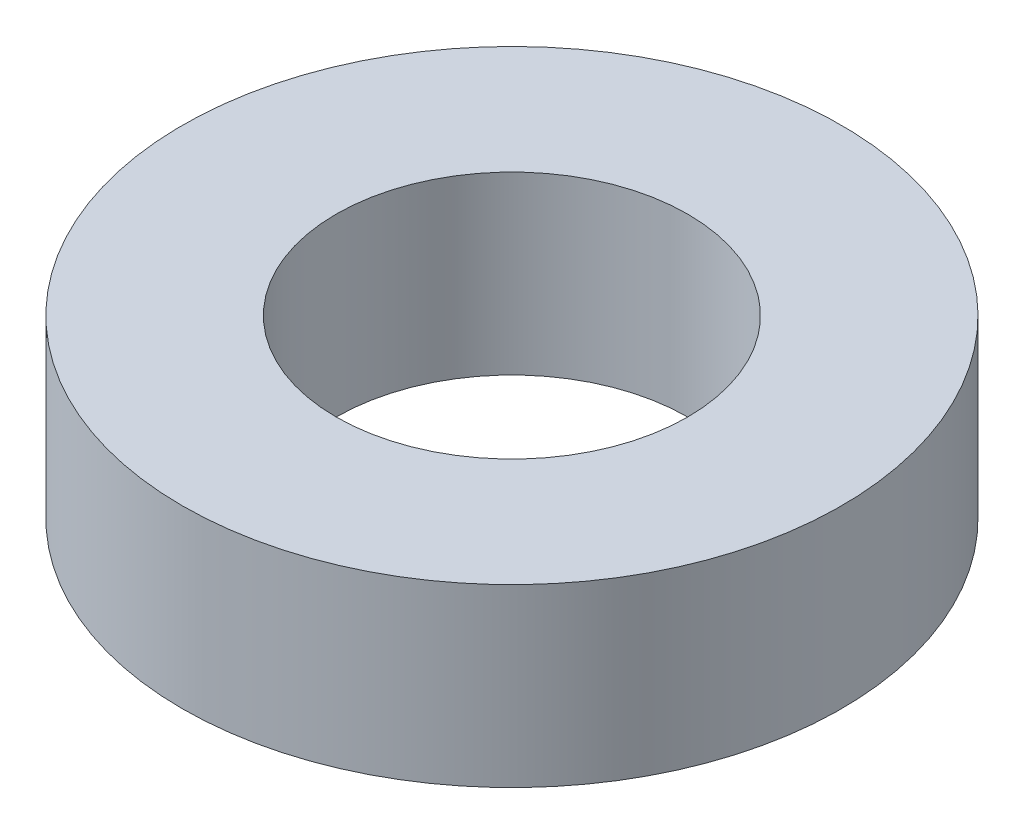
SolidWorks part; units mm, degrees
ref_plane "Front Plane" through (0, 0, 0) normal (0, 0, 1) x (1, 0, 0)
ref_plane "Top Plane" through (0, 0, 0) normal (0, 1, 0) x (1, 0, 0)
ref_plane "Right Plane" through (0, 0, 0) normal (1, 0, 0) x (0, 0, -1)
sketch "Sketch1" plane through (0, 0, 0) normal (0, 1, 0) x (1, 0, 0)
  circle A0 centre (0, 0) radius 11.9062
  circle A1 centre (0, 0) radius 6.35
  dimension "D1" = 12.7
  dimension "D2" = 23.8125
extrude "Boss-Extrude1" add sketch "Sketch1" along normal blind 6.35
